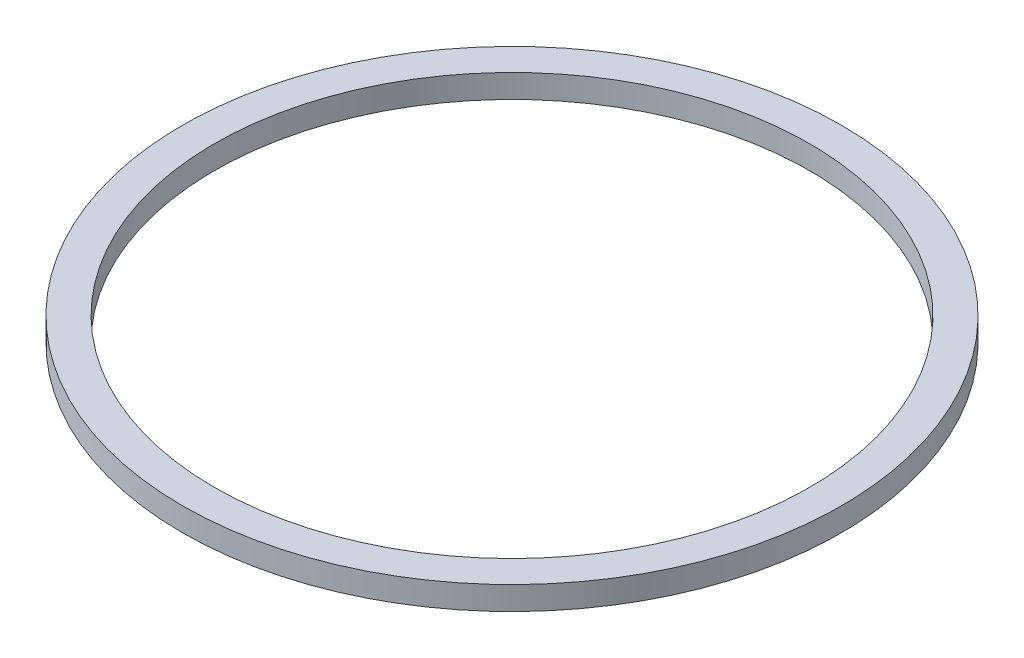
SolidWorks part; units mm, degrees
ref_plane "Front Plane" through (0, 0, 0) normal (0, 0, 1) x (1, 0, 0)
ref_plane "Top Plane" through (0, 0, 0) normal (0, 1, 0) x (1, 0, 0)
ref_plane "Right Plane" through (0, 0, 0) normal (1, 0, 0) x (0, 0, -1)
sketch "Sketch1" plane through (0, 0, 0) normal (0, 1, 0) x (1, 0, 0)
  circle A0 centre (0, 0) radius 15.5
  circle A1 centre (0, 0) radius 14
  dimension "D1" = 31
  dimension "D2" = 28
extrude "Boss-Extrude1" add sketch "Sketch1" along normal blind 1.1
